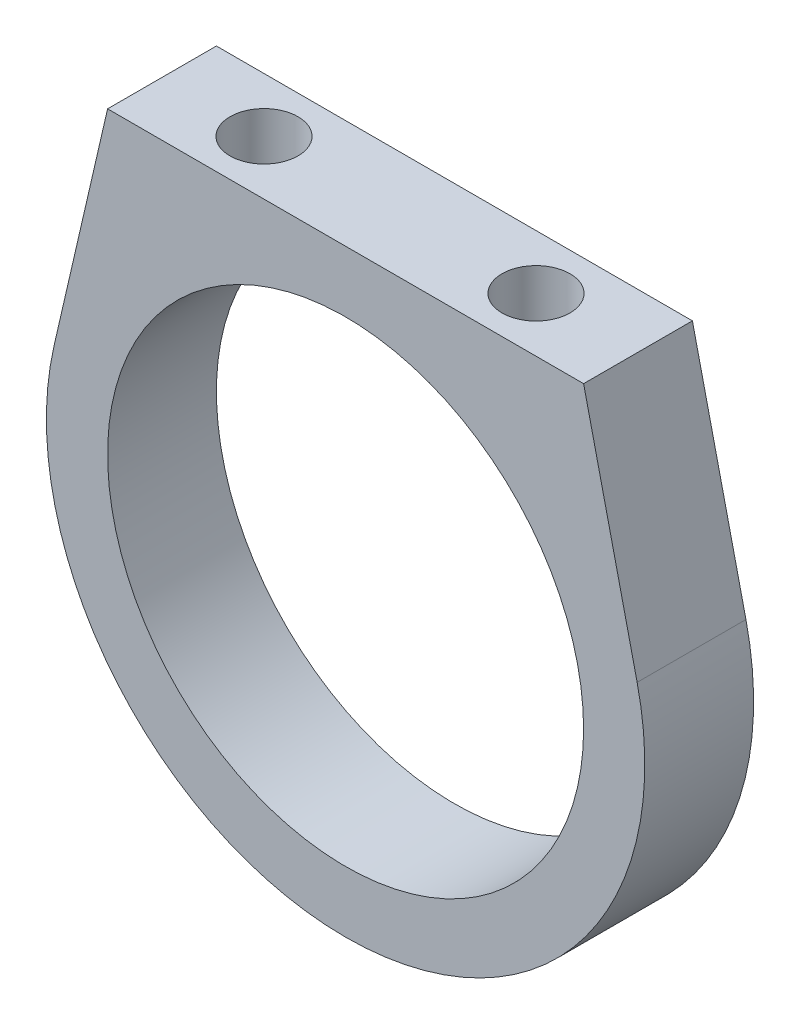
SolidWorks part; units mm, degrees
material "6063-T1"
ref_plane "Front Plane" through (0, 0, 0) normal (0, 0, 1) x (1, 0, 0)
ref_plane "Top Plane" through (0, 0, 0) normal (0, 1, 0) x (1, 0, 0)
ref_plane "Right Plane" through (0, 0, 0) normal (1, 0, 0) x (0, 0, -1)
sketch "Sketch1" plane through (0, 0, 0) normal (0, 0, 1) x (1, 0, 0)
  line L0 (8.75, 11) -> (-8.75, 11)
  line L1 (8.75, 11) -> (10.7181, 2.4742)
  line L2 (-8.75, 11) -> (-10.7181, 2.4742)
  line L4 (0, -13.5975) -> (0, 13.5975) construction
  arc A0 (10.7181, 2.4742) -> (-10.7181, 2.4742) centre (0, 0) cw
  circle A1 centre (0, 0) radius 8.75
  dimension "D4" = 17.5
  dimension "D5" = 11
  dimension "D1" = 17.5
  dimension "D2" = 11
  dimension "D3" = 8.75
extrude "Boss-Extrude1" add sketch "Sketch1" along normal mid plane 4
sketch "Sketch2" plane through (0, 11, 0) normal (0, 1, 0) x (1, 0, 0)
  line L0 (-12.1, 0) -> (12.1, 0) construction
  line L1 (8.75, -2) -> (8.75, 2) construction
  circle A0 centre (-5, 0) radius 1.25
  circle A1 centre (5, 0) radius 1.25
  dimension "D1" = 2.5
  dimension "D2" = 10
  dimension "D3" = 3.75
extrude "ThreadedHoles" cut sketch "Sketch2" against normal up to surface (4.8763 mm away)
equation "\"OuterRad\"=11"
equation "\"D5@Sketch1\"=\"OuterRad\""
equation "\"D2@Sketch1\"=\"OuterRad\""
equation "\"InnerDiameter\"=17.5"
equation "\"D4@Sketch1\"=\"InnerDiameter\""
equation "\"D1@Sketch1\"=\"InnerDiameter\""
equation "\"D3@Sketch1\"=\"InnerDiameter\"/2"
equation "\"Thick\"=4"
equation "\"D1@Boss-Extrude1\"=\"Thick\""
equation "\"ScrewDiam\"=2.5"
equation "\"D1@Sketch2\"=\"ScrewDiam\""
equation "\"ScrewDist\"=10"
equation "\"D2@Sketch2\"=\"ScrewDist\""
equation "\"D3@Sketch2\"=(\"InnerDiameter\"-\"ScrewDist\")/2"
